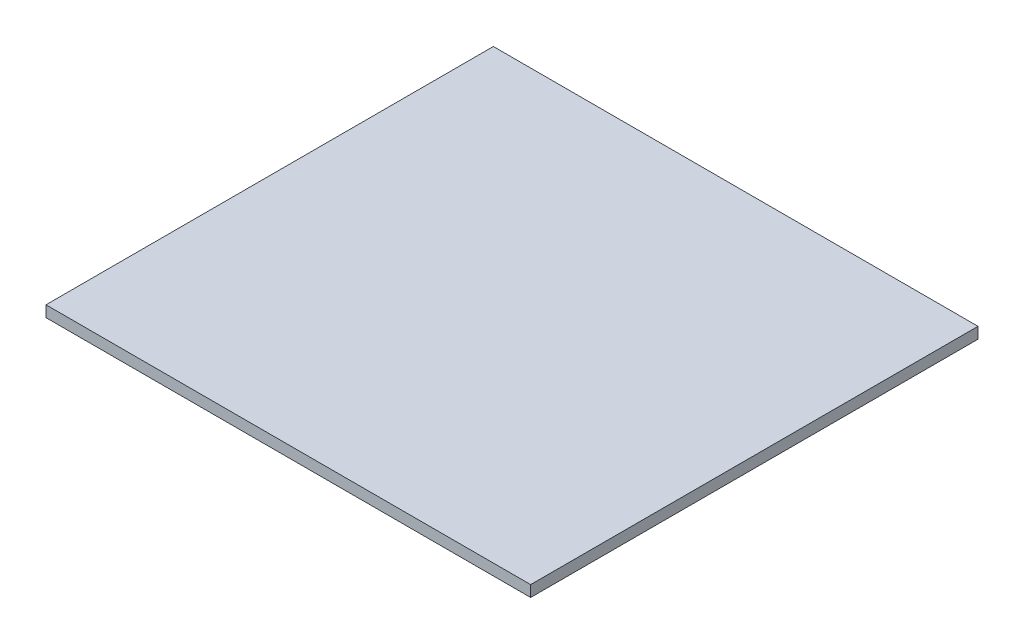
SolidWorks part; units mm, degrees
ref_plane "前基準面" through (0, 0, 0) normal (0, 0, 1) x (1, 0, 0)
ref_plane "上基準面" through (0, 0, 0) normal (0, 1, 0) x (1, 0, 0)
ref_plane "右基準面" through (0, 0, 0) normal (1, 0, 0) x (0, 0, -1)
sketch "草圖1" plane through (0, 0, 0) normal (0, 1, 0) x (1, 0, 0)
  line L1 (-130, 120) -> (0, 120)
  line L2 (-130, 120) -> (-130, 0)
  line L3 (-130, 0) -> (0, 0)
  line L4 (0, 120) -> (0, 0)
  dimension "D1" = 130
  dimension "D2" = 120
extrude "伸長1" add sketch "草圖1" along normal blind 3
